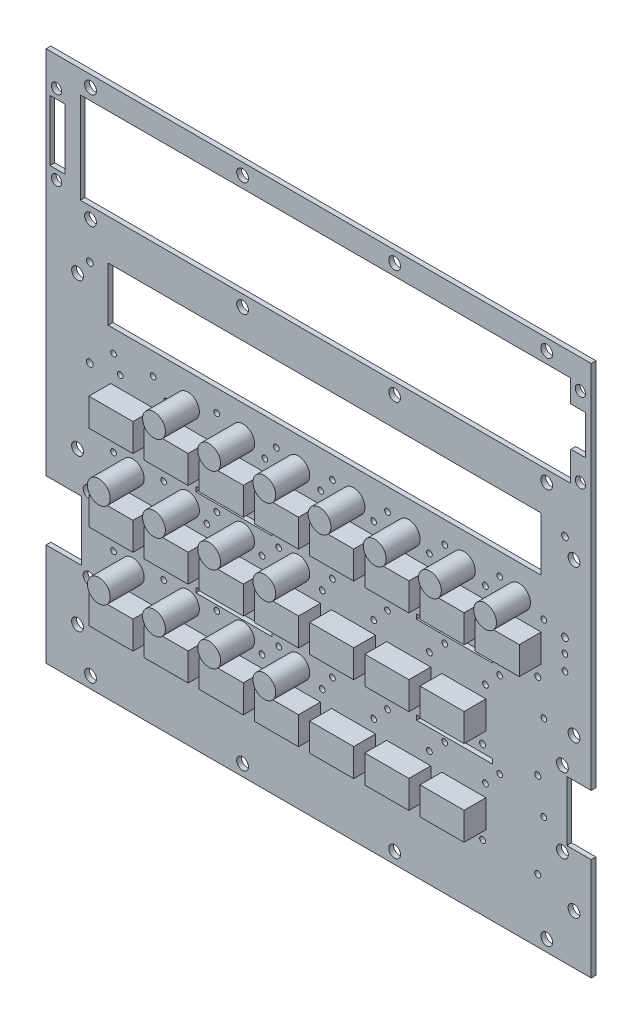
SolidWorks part; units mm, degrees
ref_plane "Front Plane" through (0, 0, 0) normal (0, 0, 1) x (1, 0, 0)
ref_plane "Top Plane" through (0, 0, 0) normal (0, 1, 0) x (1, 0, 0)
ref_plane "Right Plane" through (0, 0, 0) normal (1, 0, 0) x (0, 0, -1)
sketch "Sketch1" plane through (0, 0, 0) normal (0, 0, 1) x (1, 0, 0)
  line L0 (0, 0) -> (182.118, 0)
  line L1 (182.118, 0) -> (182.118, 34.2468)
  line L2 (182.118, 34.2468) -> (173.9875, 34.2468)
  line L3 (173.9875, 34.2468) -> (173.9875, 54.2468)
  line L4 (173.9875, 54.2468) -> (182.118, 54.2468)
  line L5 (182.118, 54.2468) -> (182.118, 177.8)
  line L6 (182.118, 177.8) -> (0, 177.8)
  line L7 (0, 177.8) -> (0, 54.2468)
  line L8 (0, 54.2468) -> (11.8694, 54.2468)
  line L9 (11.8694, 54.2468) -> (11.8694, 34.2468)
  line L10 (11.8694, 34.2468) -> (0, 34.2468)
  line L11 (0, 34.2468) -> (0, 0)
  line L12 (20.7391, 108.1786) -> (20.7391, 126.1796)
  line L13 (20.7391, 126.1796) -> (165.3007, 126.1796)
  line L14 (165.3007, 126.1796) -> (165.3007, 108.1786)
  line L15 (165.3007, 108.1786) -> (20.7391, 108.1786)
  line L16 (1.27, 144.653) -> (1.27, 164.973)
  line L17 (1.27, 164.973) -> (6.35, 164.973)
  line L18 (6.35, 164.973) -> (6.35, 144.653)
  line L19 (6.35, 144.653) -> (1.27, 144.653)
  line L20 (12.7, 170.18) -> (175.26, 170.18)
  line L21 (175.26, 170.18) -> (175.26, 162.6616)
  line L22 (175.26, 162.6616) -> (180.086, 162.6616)
  line L23 (180.086, 162.6616) -> (180.2892, 162.4584)
  line L24 (180.2892, 162.4584) -> (180.2892, 149.606)
  line L25 (180.2892, 149.606) -> (175.3616, 149.606)
  line L26 (175.3616, 149.606) -> (175.26, 149.5044)
  line L27 (175.26, 149.5044) -> (175.26, 139.7)
  line L28 (175.26, 139.7) -> (12.7, 139.7)
  line L29 (12.7, 139.7) -> (11.43, 139.7)
  line L30 (11.43, 139.7) -> (11.43, 170.18)
  line L31 (11.43, 170.18) -> (12.7, 170.18)
  line L32 (50.0634, 45.4152) -> (50.0634, 47.0027)
  line L33 (50.0634, 47.0027) -> (75.4634, 47.0027)
  line L34 (75.4634, 47.0027) -> (75.4634, 45.4152)
  line L35 (75.4634, 45.4152) -> (50.0634, 45.4152)
  line L36 (123.8134, 45.4152) -> (123.8134, 47.0027)
  line L37 (123.8134, 47.0027) -> (149.2134, 47.0027)
  line L38 (149.2134, 47.0027) -> (149.2134, 45.4152)
  line L39 (149.2134, 45.4152) -> (123.8134, 45.4152)
  line L40 (123.8134, 74.6252) -> (123.8134, 76.2127)
  line L41 (123.8134, 76.2127) -> (149.2134, 76.2127)
  line L42 (149.2134, 76.2127) -> (149.2134, 74.6252)
  line L43 (149.2134, 74.6252) -> (123.8134, 74.6252)
  line L44 (50.0634, 74.6252) -> (50.0634, 76.2127)
  line L45 (50.0634, 76.2127) -> (75.4634, 76.2127)
  line L46 (75.4634, 76.2127) -> (75.4634, 74.6252)
  line L47 (75.4634, 74.6252) -> (50.0634, 74.6252)
extrude "BOARD" add sketch "Sketch1" along normal blind 1.5921 separate body
ref_plane "Plane1" through (0, 0, 1.5921) normal (0, 0, 1) x (1, 0, 0)
sketch "Sketch11" plane through (0, 0, 1.5921) normal (0, 0, 1) x (1, 0, 0)
  circle A0 centre (84.2812, 41.1988) radius 3.81
extrude "LED-KINGBRIGHT_3P_2P54-10" add sketch "Sketch11" along normal blind 11.3538 separate body
sketch "Sketch12" plane through (0, 0, 1.5921) normal (0, 0, 1) x (1, 0, 0)
  circle A0 centre (65.8437, 41.1988) radius 3.81
extrude "LED-KINGBRIGHT_3P_2P54-11" add sketch "Sketch12" along normal blind 11.3538 separate body
sketch "Sketch13" plane through (0, 0, 1.5921) normal (0, 0, 1) x (1, 0, 0)
  circle A0 centre (47.4062, 41.1988) radius 3.81
extrude "LED-KINGBRIGHT_3P_2P54-12" add sketch "Sketch13" along normal blind 11.3538 separate body
sketch "Sketch14" plane through (0, 0, 1.5921) normal (0, 0, 1) x (1, 0, 0)
  circle A0 centre (28.9687, 41.1988) radius 3.81
extrude "LED-KINGBRIGHT_3P_2P54-13" add sketch "Sketch14" along normal blind 11.3538 separate body
sketch "Sketch15" plane through (0, 0, 1.5921) normal (0, 0, 1) x (1, 0, 0)
  circle A0 centre (84.2812, 69.7738) radius 3.81
extrude "LED-KINGBRIGHT_3P_2P54-14" add sketch "Sketch15" along normal blind 11.3538 separate body
sketch "Sketch16" plane through (0, 0, 1.5921) normal (0, 0, 1) x (1, 0, 0)
  circle A0 centre (65.8437, 69.7738) radius 3.81
extrude "LED-KINGBRIGHT_3P_2P54-15" add sketch "Sketch16" along normal blind 11.3538 separate body
sketch "Sketch17" plane through (0, 0, 1.5921) normal (0, 0, 1) x (1, 0, 0)
  circle A0 centre (47.4062, 69.7738) radius 3.81
extrude "LED-KINGBRIGHT_3P_2P54-16" add sketch "Sketch17" along normal blind 11.3538 separate body
sketch "Sketch18" plane through (0, 0, 1.5921) normal (0, 0, 1) x (1, 0, 0)
  circle A0 centre (28.9687, 69.7738) radius 3.81
extrude "LED-KINGBRIGHT_3P_2P54-17" add sketch "Sketch18" along normal blind 11.3538 separate body
sketch "Sketch19" plane through (0, 0, 1.5921) normal (0, 0, 1) x (1, 0, 0)
  circle A0 centre (158.0312, 98.3488) radius 3.81
extrude "LED-KINGBRIGHT_3P_2P54-18" add sketch "Sketch19" along normal blind 11.3538 separate body
sketch "Sketch20" plane through (0, 0, 1.5921) normal (0, 0, 1) x (1, 0, 0)
  circle A0 centre (139.5937, 98.3488) radius 3.81
extrude "LED-KINGBRIGHT_3P_2P54-19" add sketch "Sketch20" along normal blind 11.3538 separate body
sketch "Sketch21" plane through (0, 0, 1.5921) normal (0, 0, 1) x (1, 0, 0)
  circle A0 centre (121.1562, 98.3488) radius 3.81
extrude "LED-KINGBRIGHT_3P_2P54-20" add sketch "Sketch21" along normal blind 11.3538 separate body
sketch "Sketch22" plane through (0, 0, 1.5921) normal (0, 0, 1) x (1, 0, 0)
  circle A0 centre (102.7187, 98.3488) radius 3.81
extrude "LED-KINGBRIGHT_3P_2P54-21" add sketch "Sketch22" along normal blind 11.3538 separate body
sketch "Sketch23" plane through (0, 0, 1.5921) normal (0, 0, 1) x (1, 0, 0)
  circle A0 centre (84.2812, 98.3488) radius 3.81
extrude "LED-KINGBRIGHT_3P_2P54-22" add sketch "Sketch23" along normal blind 11.3538 separate body
sketch "Sketch24" plane through (0, 0, 1.5921) normal (0, 0, 1) x (1, 0, 0)
  circle A0 centre (65.8437, 98.3488) radius 3.81
extrude "LED-KINGBRIGHT_3P_2P54-23" add sketch "Sketch24" along normal blind 11.3538 separate body
sketch "Sketch25" plane through (0, 0, 1.5921) normal (0, 0, 1) x (1, 0, 0)
  circle A0 centre (47.4062, 98.3488) radius 3.81
extrude "LED-KINGBRIGHT_3P_2P54-24" add sketch "Sketch25" along normal blind 11.3538 separate body
sketch "Sketch26" plane through (0, 0, 1.5921) normal (0, 0, 1) x (1, 0, 0)
  circle A0 centre (28.9687, 98.3488) radius 3.81
sketch "Sketch29" plane through (0, 0, 1.5921) normal (0, 0, 1) x (1, 0, 0)
  line L0 (132.2277, 25.3238) -> (132.2277, 34.5948)
  line L1 (132.2277, 34.5948) -> (146.9597, 34.5948)
  line L2 (146.9597, 34.5948) -> (146.9597, 25.3238)
  line L3 (146.9597, 25.3238) -> (132.2277, 25.3238)
extrude "SWITCH-MCDTS2-3" add sketch "Sketch29" along normal blind 7.3 separate body
sketch "Sketch30" plane through (0, 0, 1.5921) normal (0, 0, 1) x (1, 0, 0)
  line L0 (113.7902, 25.3238) -> (113.7902, 34.5948)
  line L1 (113.7902, 34.5948) -> (128.5222, 34.5948)
  line L2 (128.5222, 34.5948) -> (128.5222, 25.3238)
  line L3 (128.5222, 25.3238) -> (113.7902, 25.3238)
extrude "SWITCH-MCDTS2-4" add sketch "Sketch30" along normal blind 7.3 separate body
sketch "Sketch31" plane through (0, 0, 1.5921) normal (0, 0, 1) x (1, 0, 0)
  line L0 (95.3527, 25.3238) -> (95.3527, 34.5948)
  line L1 (95.3527, 34.5948) -> (110.0847, 34.5948)
  line L2 (110.0847, 34.5948) -> (110.0847, 25.3238)
  line L3 (110.0847, 25.3238) -> (95.3527, 25.3238)
extrude "SWITCH-MCDTS2-5" add sketch "Sketch31" along normal blind 7.3 separate body
sketch "Sketch32" plane through (0, 0, 1.5921) normal (0, 0, 1) x (1, 0, 0)
  line L0 (76.9152, 25.3238) -> (76.9152, 34.5948)
  line L1 (76.9152, 34.5948) -> (91.6472, 34.5948)
  line L2 (91.6472, 34.5948) -> (91.6472, 25.3238)
  line L3 (91.6472, 25.3238) -> (76.9152, 25.3238)
extrude "SWITCH-MCDTS2-6" add sketch "Sketch32" along normal blind 7.3 separate body
sketch "Sketch33" plane through (0, 0, 1.5921) normal (0, 0, 1) x (1, 0, 0)
  line L0 (58.4777, 25.3238) -> (58.4777, 34.5948)
  line L1 (58.4777, 34.5948) -> (73.2097, 34.5948)
  line L2 (73.2097, 34.5948) -> (73.2097, 25.3238)
  line L3 (73.2097, 25.3238) -> (58.4777, 25.3238)
extrude "SWITCH-MCDTS2-7" add sketch "Sketch33" along normal blind 7.3 separate body
sketch "Sketch34" plane through (0, 0, 1.5921) normal (0, 0, 1) x (1, 0, 0)
  line L0 (40.0402, 25.3238) -> (40.0402, 34.5948)
  line L1 (40.0402, 34.5948) -> (54.7722, 34.5948)
  line L2 (54.7722, 34.5948) -> (54.7722, 25.3238)
  line L3 (54.7722, 25.3238) -> (40.0402, 25.3238)
extrude "SWITCH-MCDTS2-8" add sketch "Sketch34" along normal blind 7.3 separate body
sketch "Sketch35" plane through (0, 0, 1.5921) normal (0, 0, 1) x (1, 0, 0)
  line L0 (21.6027, 25.3238) -> (21.6027, 34.5948)
  line L1 (21.6027, 34.5948) -> (36.3347, 34.5948)
  line L2 (36.3347, 34.5948) -> (36.3347, 25.3238)
  line L3 (36.3347, 25.3238) -> (21.6027, 25.3238)
extrude "SWITCH-MCDTS2-9" add sketch "Sketch35" along normal blind 7.3 separate body
sketch "Sketch36" plane through (0, 0, 1.5921) normal (0, 0, 1) x (1, 0, 0)
  line L0 (132.2277, 53.8988) -> (132.2277, 63.1698)
  line L1 (132.2277, 63.1698) -> (146.9597, 63.1698)
  line L2 (146.9597, 63.1698) -> (146.9597, 53.8988)
  line L3 (146.9597, 53.8988) -> (132.2277, 53.8988)
extrude "SWITCH-MCDTS2-10" add sketch "Sketch36" along normal blind 7.3 separate body
sketch "Sketch37" plane through (0, 0, 1.5921) normal (0, 0, 1) x (1, 0, 0)
  line L0 (113.7902, 53.8988) -> (113.7902, 63.1698)
  line L1 (113.7902, 63.1698) -> (128.5222, 63.1698)
  line L2 (128.5222, 63.1698) -> (128.5222, 53.8988)
  line L3 (128.5222, 53.8988) -> (113.7902, 53.8988)
extrude "SWITCH-MCDTS2-11" add sketch "Sketch37" along normal blind 7.3 separate body
sketch "Sketch38" plane through (0, 0, 1.5921) normal (0, 0, 1) x (1, 0, 0)
  line L0 (95.3527, 53.8988) -> (95.3527, 63.1698)
  line L1 (95.3527, 63.1698) -> (110.0847, 63.1698)
  line L2 (110.0847, 63.1698) -> (110.0847, 53.8988)
  line L3 (110.0847, 53.8988) -> (95.3527, 53.8988)
extrude "SWITCH-MCDTS2-12" add sketch "Sketch38" along normal blind 7.3 separate body
sketch "Sketch39" plane through (0, 0, 1.5921) normal (0, 0, 1) x (1, 0, 0)
  line L0 (76.9152, 53.8988) -> (76.9152, 63.1698)
  line L1 (76.9152, 63.1698) -> (91.6472, 63.1698)
  line L2 (91.6472, 63.1698) -> (91.6472, 53.8988)
  line L3 (91.6472, 53.8988) -> (76.9152, 53.8988)
extrude "SWITCH-MCDTS2-13" add sketch "Sketch39" along normal blind 7.3 separate body
sketch "Sketch40" plane through (0, 0, 1.5921) normal (0, 0, 1) x (1, 0, 0)
  line L0 (58.4777, 53.8988) -> (58.4777, 63.1698)
  line L1 (58.4777, 63.1698) -> (73.2097, 63.1698)
  line L2 (73.2097, 63.1698) -> (73.2097, 53.8988)
  line L3 (73.2097, 53.8988) -> (58.4777, 53.8988)
extrude "SWITCH-MCDTS2-14" add sketch "Sketch40" along normal blind 7.3 separate body
sketch "Sketch41" plane through (0, 0, 1.5921) normal (0, 0, 1) x (1, 0, 0)
  line L0 (40.0402, 53.8988) -> (40.0402, 63.1698)
  line L1 (40.0402, 63.1698) -> (54.7722, 63.1698)
  line L2 (54.7722, 63.1698) -> (54.7722, 53.8988)
  line L3 (54.7722, 53.8988) -> (40.0402, 53.8988)
extrude "SWITCH-MCDTS2-15" add sketch "Sketch41" along normal blind 7.3 separate body
sketch "Sketch42" plane through (0, 0, 1.5921) normal (0, 0, 1) x (1, 0, 0)
  line L0 (21.6027, 53.8988) -> (21.6027, 63.1698)
  line L1 (21.6027, 63.1698) -> (36.3347, 63.1698)
  line L2 (36.3347, 63.1698) -> (36.3347, 53.8988)
  line L3 (36.3347, 53.8988) -> (21.6027, 53.8988)
extrude "SWITCH-MCDTS2-16" add sketch "Sketch42" along normal blind 7.3 separate body
sketch "Sketch43" plane through (0, 0, 1.5921) normal (0, 0, 1) x (1, 0, 0)
  line L0 (150.6652, 82.4738) -> (150.6652, 91.7448)
  line L1 (150.6652, 91.7448) -> (165.3972, 91.7448)
  line L2 (165.3972, 91.7448) -> (165.3972, 82.4738)
  line L3 (165.3972, 82.4738) -> (150.6652, 82.4738)
extrude "SWITCH-MCDTS2-17" add sketch "Sketch43" along normal blind 7.3 separate body
sketch "Sketch44" plane through (0, 0, 1.5921) normal (0, 0, 1) x (1, 0, 0)
  line L0 (132.2277, 82.4738) -> (132.2277, 91.7448)
  line L1 (132.2277, 91.7448) -> (146.9597, 91.7448)
  line L2 (146.9597, 91.7448) -> (146.9597, 82.4738)
  line L3 (146.9597, 82.4738) -> (132.2277, 82.4738)
extrude "SWITCH-MCDTS2-18" add sketch "Sketch44" along normal blind 7.3 separate body
sketch "Sketch45" plane through (0, 0, 1.5921) normal (0, 0, 1) x (1, 0, 0)
  line L0 (113.7902, 82.4738) -> (113.7902, 91.7448)
  line L1 (113.7902, 91.7448) -> (128.5222, 91.7448)
  line L2 (128.5222, 91.7448) -> (128.5222, 82.4738)
  line L3 (128.5222, 82.4738) -> (113.7902, 82.4738)
extrude "SWITCH-MCDTS2-19" add sketch "Sketch45" along normal blind 7.3 separate body
sketch "Sketch46" plane through (0, 0, 1.5921) normal (0, 0, 1) x (1, 0, 0)
  line L0 (95.3527, 82.4738) -> (95.3527, 91.7448)
  line L1 (95.3527, 91.7448) -> (110.0847, 91.7448)
  line L2 (110.0847, 91.7448) -> (110.0847, 82.4738)
  line L3 (110.0847, 82.4738) -> (95.3527, 82.4738)
extrude "SWITCH-MCDTS2-20" add sketch "Sketch46" along normal blind 7.3 separate body
sketch "Sketch47" plane through (0, 0, 1.5921) normal (0, 0, 1) x (1, 0, 0)
  line L0 (76.9152, 82.4738) -> (76.9152, 91.7448)
  line L1 (76.9152, 91.7448) -> (91.6472, 91.7448)
  line L2 (91.6472, 91.7448) -> (91.6472, 82.4738)
  line L3 (91.6472, 82.4738) -> (76.9152, 82.4738)
extrude "SWITCH-MCDTS2-21" add sketch "Sketch47" along normal blind 7.3 separate body
sketch "Sketch48" plane through (0, 0, 1.5921) normal (0, 0, 1) x (1, 0, 0)
  line L0 (58.4777, 82.4738) -> (58.4777, 91.7448)
  line L1 (58.4777, 91.7448) -> (73.2097, 91.7448)
  line L2 (73.2097, 91.7448) -> (73.2097, 82.4738)
  line L3 (73.2097, 82.4738) -> (58.4777, 82.4738)
extrude "SWITCH-MCDTS2-22" add sketch "Sketch48" along normal blind 7.3 separate body
sketch "Sketch49" plane through (0, 0, 1.5921) normal (0, 0, 1) x (1, 0, 0)
  line L0 (40.0402, 82.4738) -> (40.0402, 91.7448)
  line L1 (40.0402, 91.7448) -> (54.7722, 91.7448)
  line L2 (54.7722, 91.7448) -> (54.7722, 82.4738)
  line L3 (54.7722, 82.4738) -> (40.0402, 82.4738)
extrude "SWITCH-MCDTS2-23" add sketch "Sketch49" along normal blind 7.3 separate body
sketch "Sketch50" plane through (0, 0, 1.5921) normal (0, 0, 1) x (1, 0, 0)
  line L0 (21.6027, 82.4738) -> (21.6027, 91.7448)
  line L1 (21.6027, 91.7448) -> (36.3347, 91.7448)
  line L2 (36.3347, 91.7448) -> (36.3347, 82.4738)
  line L3 (36.3347, 82.4738) -> (21.6027, 82.4738)
extrude "SWITCH-MCDTS2-24" add sketch "Sketch50" along normal blind 7.3 separate body
sketch "Sketch52" plane through (0, 0, 1.5921) normal (0, 0, 1) x (1, 0, 0)
  line L0 (0, 34.2468) -> (0, 0) construction
  line L1 (0, 0) -> (182.118, 0) construction
  circle B0 centre (164.2745, 21.1074) radius 1.016
  circle B1 centre (164.2745, 49.6824) radius 1.016
  circle B2 centre (145.8341, 21.8186) radius 0.9652
  circle B3 centre (127.4191, 21.6154) radius 0.9652
  circle B4 centre (108.9787, 21.7424) radius 0.9652
  circle B5 centre (90.5383, 21.844) radius 0.9652
  circle B6 centre (72.0979, 20.7772) radius 0.9652
  circle B7 centre (53.6575, 21.1582) radius 0.9652
  circle B8 centre (35.2187, 21.1328) radius 1.016
  circle B9 centre (145.8341, 49.5554) radius 1.016
  circle B10 centre (127.3937, 49.3522) radius 1.016
  circle B11 centre (108.9533, 49.1236) radius 1.016
  circle B12 centre (90.5129, 49.6824) radius 1.016
  circle B13 centre (72.0725, 49.1998) radius 1.016
  circle B14 centre (53.6321, 49.1998) radius 1.016
  circle B15 centre (35.1917, 49.276) radius 1.016
  circle B16 centre (164.2745, 78.2574) radius 1.016
  circle B17 centre (145.8341, 77.7748) radius 1.016
  circle B18 centre (127.3175, 78.3336) radius 1.016
  circle B19 centre (108.9533, 78.74) radius 1.016
  circle B20 centre (90.5129, 78.3336) radius 1.016
  circle B21 centre (72.0725, 78.2574) radius 1.016
  circle B22 centre (53.6321, 78.4098) radius 1.016
  circle B23 centre (35.1917, 78.0542) radius 1.016
  circle B24 centre (92.2655, 38.6588) radius 0.9525
  circle B25 centre (77.7367, 43.7388) radius 0.9525
  circle B26 centre (72.1487, 38.6588) radius 0.9525
  circle B27 centre (57.0611, 43.7388) radius 0.9525
  circle B28 centre (39.3065, 43.7388) radius 0.9525
  circle B29 centre (22.4663, 38.6588) radius 0.9525
  circle B30 centre (22.5425, 43.7388) radius 0.9525
  circle B31 centre (77.7367, 72.3138) radius 0.9525
  circle B32 centre (92.2655, 67.2338) radius 0.9525
  circle B33 centre (72.1487, 67.2338) radius 0.9525
  circle B34 centre (57.0611, 72.3138) radius 0.9525
  circle B35 centre (53.7083, 67.2338) radius 0.9525
  circle B36 centre (39.3065, 72.3138) radius 0.9525
  circle B37 centre (22.4663, 67.2338) radius 0.9525
  circle B38 centre (22.5425, 72.3138) radius 0.9525
  circle B39 centre (166.3065, 95.8088) radius 0.9525
  circle B40 centre (151.5491, 100.8888) radius 0.9525
  circle B41 centre (146.7993, 95.8088) radius 0.9525
  circle B42 centre (133.1849, 100.8888) radius 0.9525
  circle B43 centre (114.0587, 100.8888) radius 0.9525
  circle B44 centre (128.0795, 95.8088) radius 0.9525
  circle B45 centre (109.4359, 95.8088) radius 0.9525
  circle B46 centre (95.6691, 100.8888) radius 0.9525
  circle B47 centre (91.7575, 95.8088) radius 0.9525
  circle B48 centre (76.9493, 100.8888) radius 0.9525
  circle B49 centre (73.1139, 95.8088) radius 0.9525
  circle B50 centre (56.9849, 100.8888) radius 0.9525
  circle B51 centre (40.2971, 95.8088) radius 0.9525
  circle B52 centre (35.7505, 100.8888) radius 0.9525
  circle B53 centre (24.7777, 95.8088) radius 0.9525
  circle B54 centre (22.5425, 100.8888) radius 0.9525
  circle B55 centre (133.1849, 72.3138) radius 0.9525
  circle B56 centre (146.7993, 67.2338) radius 0.9525
  circle B57 centre (114.0587, 72.3138) radius 0.9525
  circle B58 centre (128.0795, 67.2338) radius 0.9525
  circle B59 centre (95.6691, 72.3138) radius 0.9525
  circle B60 centre (109.4359, 67.2338) radius 0.9525
  circle B61 centre (151.5491, 43.7388) radius 0.9525
  circle B62 centre (133.1849, 43.7388) radius 0.9525
  circle B63 centre (114.0587, 43.7388) radius 0.9525
  circle B64 centre (95.6691, 43.7388) radius 0.9525
  circle B65 centre (109.4359, 38.6588) radius 0.9525
  circle B66 centre (151.5491, 72.3138) radius 0.9525
  circle B67 centre (166.3065, 67.2338) radius 0.9525
  circle B68 centre (173.3296, 89.4588) radius 0.9525
  circle B69 centre (173.355, 84.3534) radius 0.9525
  circle B70 centre (176.3725, 118.11) radius 1.9685
  circle B71 centre (176.3725, 67.31) radius 1.9685
  circle B72 centre (176.3725, 16.51) radius 1.9685
  circle B73 centre (167.259, 135.89) radius 1.9685
  circle B74 centre (116.459, 135.89) radius 1.9685
  circle B75 centre (65.659, 135.89) radius 1.9685
  circle B76 centre (14.859, 135.89) radius 1.9685
  circle B77 centre (10.5105, 118.11) radius 1.9685
  circle B78 centre (10.5105, 67.31) radius 1.9685
  circle B79 centre (10.5105, 16.51) radius 1.9685
  circle B80 centre (166.3065, 38.6588) radius 0.9525
  circle B81 centre (146.7993, 38.6588) radius 0.9525
  circle B82 centre (128.0795, 38.6588) radius 0.9525
  circle B83 centre (14.859, 173.99) radius 1.9685
  circle B84 centre (65.659, 173.99) radius 1.9685
  circle B85 centre (116.459, 173.99) radius 1.9685
  circle B86 centre (167.259, 173.99) radius 1.9685
  circle B87 centre (167.259, 3.81) radius 1.9685
  circle B88 centre (116.459, 3.81) radius 1.9685
  circle B89 centre (65.659, 3.81) radius 1.9685
  circle B90 centre (14.859, 3.81) radius 1.9685
  circle B91 centre (172.5066, 56.7436) radius 1.9685
  circle B92 centre (172.5066, 31.75) radius 1.9685
  circle B93 centre (14.3688, 56.7436) radius 1.9685
  circle B94 centre (14.3688, 31.75) radius 1.9685
  circle B95 centre (173.3575, 123.3754) radius 1.1303
  circle B96 centre (173.3575, 94.1654) radius 1.1303
  circle B97 centre (14.6075, 94.1654) radius 1.1303
  circle B98 centre (14.6075, 123.3754) radius 1.1303
  circle B99 centre (178.5137, 141.5618) radius 1.7145
  circle B100 centre (178.5137, 168.0616) radius 1.7145
  circle B101 centre (3.5001, 168.0616) radius 1.7145
  circle B102 centre (3.5001, 141.5618) radius 1.7145
  dimension "D1" = 14.859
  dimension "D2" = 3.81
sketch_block_instance "Block1-4"
sketch_block "Block1"
extrude "Cut-Extrude1" cut sketch "Sketch52" against normal blind 2.54
